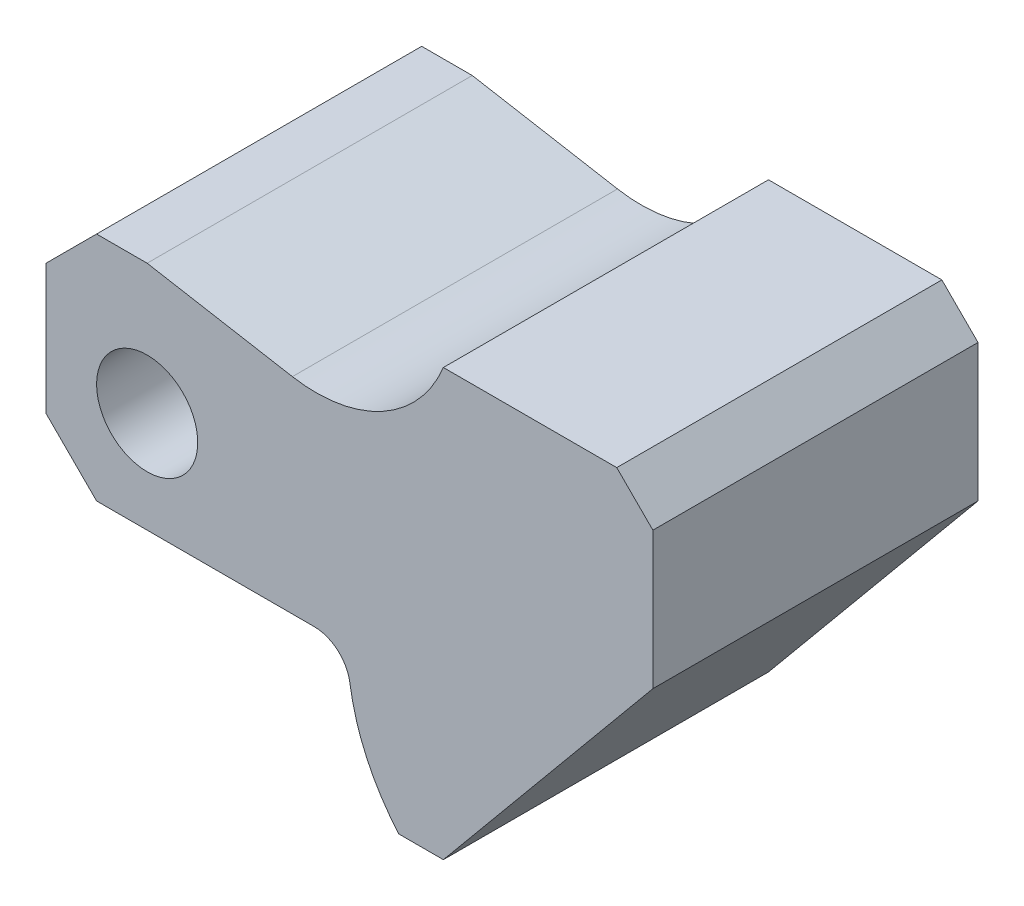
SolidWorks part; units mm, degrees
material "AISI 1020"
ref_plane "Front Plane" through (0, 0, 0) normal (0, 0, 1) x (1, 0, 0)
ref_plane "Top Plane" through (0, 0, 0) normal (0, 1, 0) x (1, 0, 0)
ref_plane "Right Plane" through (0, 0, 0) normal (1, 0, 0) x (0, 0, -1)
sketch "Sketch1" plane through (0, 0, 0) normal (0, 0, 1) x (1, 0, 0)
  line L0 (0, 7) -> (0, 25)
  line L1 (7, 32) -> (14, 32)
  line L2 (14, 32) -> (34.104, 28.4551)
  line L3 (55, 40) -> (79, 40)
  line L4 (84, 35) -> (84, 16)
  line L5 (84, 16) -> (55, -19)
  line L6 (55, -19) -> (48.834, -19)
  line L7 (37.1125, 0) -> (7, 0)
  line L8 (0, 25) -> (7, 32)
  line L9 (7, 0) -> (0, 7)
  line L10 (79, 40) -> (84, 35)
  arc A0 (34.104, 28.4551) -> (55, 40) centre (37.4034, 47.1665) ccw
  arc A1 (37.1125, 0) -> (42.0582, -4.2647) centre (37.1125, -5) cw
  arc A2 (42.0582, -4.2647) -> (48.834, -19) centre (70.7429, 0) ccw
  circle A3 centre (14, 14) radius 7
  point P0 (0, 0)
  point P1 (0, 32)
  point P9 (84, 40)
  dimension "D8" = 19
  dimension "D15" = 5
  dimension "D16" = 29
  dimension "D19" = 14
  dimension "D1" = 84
  dimension "D2" = 59
  dimension "D3" = 32
  dimension "D4" = 14
  dimension "D5" = 10
  dimension "D9" = 29
  dimension "D10" = 24
  dimension "D11" = 29
  dimension "D12" = 19
  dimension "D14" = 19
  dimension "D17" = 14
  dimension "D18" = 14
extrude "Boss-Extrude1" add sketch "Sketch1" along normal blind 45
equation "\"A\" = 84"
equation "\"B\" = 59"
equation "\"C\"= 45"
equation "\"D1@Sketch1\"=\"A\""
equation "\"D2@Sketch1\"=\"B\""
equation "\"D1@Boss-Extrude1\"=\"C\""
